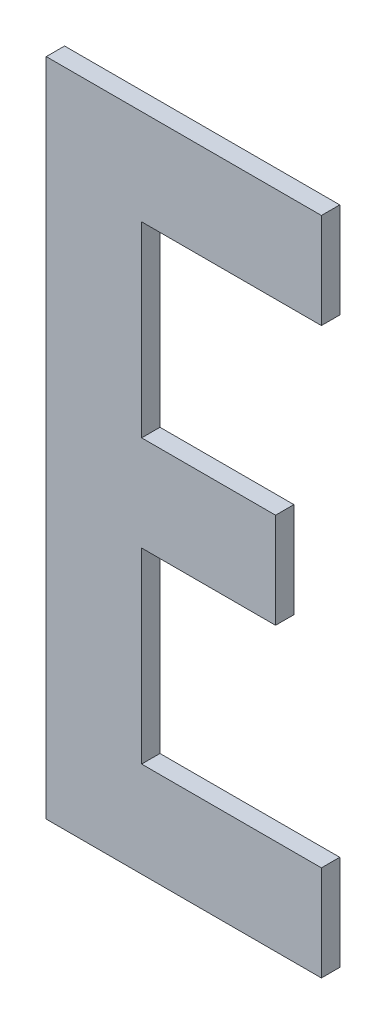
SolidWorks part; units mm, degrees
ref_plane "Front Plane" through (0, 0, 0) normal (0, 0, 1) x (1, 0, 0)
ref_plane "Top Plane" through (0, 0, 0) normal (0, 1, 0) x (1, 0, 0)
ref_plane "Right Plane" through (0, 0, 0) normal (1, 0, 0) x (0, 0, -1)
sketch "Sketch1" plane through (0, 0, 0) normal (0, 0, 1) x (1, 0, 0)
  line L0 (0, 374.5662) -> (0, -539.8338)
  line L1 (0, 374.5662) -> (381, 374.5662)
  line L2 (381, 374.5662) -> (381, 242.4862)
  line L3 (381, 242.4862) -> (132.08, 242.4862)
  line L4 (132.08, 242.4862) -> (132.08, -16.5938)
  line L5 (132.08, -16.5938) -> (317.5, -16.5938)
  line L6 (317.5, -16.5938) -> (317.5, -148.6738)
  line L7 (317.5, -148.6738) -> (132.08, -148.6738)
  line L8 (132.08, -148.6738) -> (132.08, -407.7538)
  line L9 (132.08, -407.7538) -> (381, -407.7538)
  line L10 (381, -407.7538) -> (381, -539.8338)
  line L11 (381, -539.8338) -> (0, -539.8338)
  dimension "D1" = 914.4
  dimension "D2" = 381
  dimension "D3" = 317.5
  dimension "D4" = 132.08
  dimension "D5" = 132.08
  dimension "D6" = 132.08
  dimension "D7" = 132.08
  dimension "D8" = 132.08
  dimension "D9" = 259.08
extrude "Boss-Extrude1" add sketch "Sketch1" along normal blind 25.4
